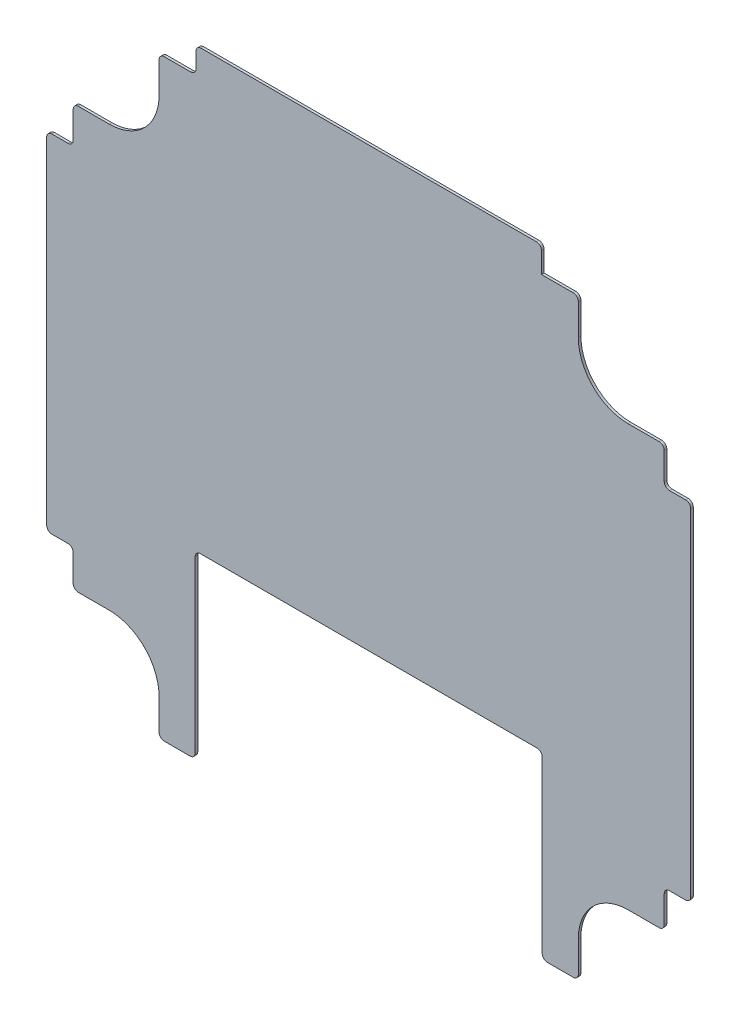
SolidWorks part; units mm, degrees
material "ABS PC"
ref_plane "Plano frontal" through (0, 0, 0) normal (0, 0, 1) x (1, 0, 0)
ref_plane "Plano superior" through (0, 0, 0) normal (0, 1, 0) x (1, 0, 0)
ref_plane "Plano direito" through (0, 0, 0) normal (1, 0, 0) x (0, 0, -1)
sketch "Esboço1" plane through (0, 0, 0) normal (0, 0, 1) x (1, 0, 0)
  line L0 (306.3428, -674.4933) -> (275.5206, -674.4933)
  line L5 (275.5206, -674.4933) -> (275.5206, -717.7786)
  line L6 (175.5581, -775.7411) -> (175.5581, -817.7411)
  line L7 (175.5581, -817.7411) -> (133.5581, -817.7411)
  line L8 (133.5581, -817.7411) -> (133.5581, -607.7411)
  line L9 (233.5206, -717.7786) -> (275.5206, -717.7786)
  line L10 (291.5428, -270.1036) -> (291.5428, -675.5786) construction
  line L12 (291.5428, -472.8411) -> (-428.2572, -472.8411) construction
  line L14 (-428.2572, -675.5786) -> (-428.2572, -472.8411) construction
  line L16 (233.5206, -227.9036) -> (275.5206, -227.9036)
  line L18 (175.5581, -127.9411) -> (133.5581, -127.9411)
  line L19 (175.5581, -169.9411) -> (175.5581, -127.9411)
  line L20 (275.5206, -271.189) -> (275.5206, -227.9036)
  line L21 (306.3428, -271.189) -> (275.5206, -271.189)
  line L23 (132.6775, -97.9411) -> (132.6775, -127.9411)
  line L24 (132.6775, -127.9411) -> (133.5581, -127.9411)
  line L26 (-68.3572, -472.8411) -> (-68.3572, -97.9411) construction
  line L27 (-428.2572, -270.1036) -> (-428.2572, -675.5786) construction
  line L28 (-269.3919, -127.9411) -> (-270.2725, -127.9411)
  line L29 (-269.3919, -97.9411) -> (-269.3919, -127.9411)
  line L30 (-443.0572, -271.189) -> (-412.235, -271.189)
  line L31 (-412.235, -271.189) -> (-412.235, -227.9036)
  line L32 (-312.2725, -169.9411) -> (-312.2725, -127.9411)
  line L33 (-312.2725, -127.9411) -> (-270.2725, -127.9411)
  line L34 (-370.235, -227.9036) -> (-412.235, -227.9036)
  line L35 (-370.235, -717.7786) -> (-412.235, -717.7786)
  line L36 (-270.2725, -817.7411) -> (-270.2725, -607.7411)
  line L37 (-312.2725, -817.7411) -> (-270.2725, -817.7411)
  line L38 (-312.2725, -775.7411) -> (-312.2725, -817.7411)
  line L39 (-412.235, -674.4933) -> (-412.235, -717.7786)
  line L40 (-443.0572, -674.4933) -> (-412.235, -674.4933)
  line L41 (-269.3919, -97.9411) -> (132.6775, -97.9411)
  line L42 (306.3428, -271.189) -> (306.3428, -674.4933)
  line L43 (-443.0572, -271.189) -> (-443.0572, -674.4933)
  line L44 (-270.2725, -607.7411) -> (133.5581, -607.7411)
  arc A0 (233.5206, -717.7786) -> (175.5581, -775.7411) centre (233.5206, -775.7411) ccw
  arc A1 (233.5206, -227.9036) -> (175.5581, -169.9411) centre (233.5206, -169.9411) cw
  arc A2 (-370.235, -227.9036) -> (-312.2725, -169.9411) centre (-370.235, -169.9411) ccw
  arc A3 (-370.235, -717.7786) -> (-312.2725, -775.7411) centre (-370.235, -775.7411) cw
  dimension "D1" = 42
  dimension "D2" = 210
  dimension "D4" = 42
extrude "Ressalto-extrusão1" add sketch "Esboço1" along normal blind 3
fillet "Filete1" radius 6 23 edges at (-443.0572, -271.189, 1.5) (-412.235, -271.189, 1.5) (-412.235, -227.9036, 1.5) (-312.2725, -127.9411, 1.5) (-269.3919, -127.9411, 1.5) (-269.3919, -97.9411, 1.5) (132.6775, -97.9411, 1.5) (175.5581, -127.9411, 1.5) (275.5206, -227.9036, 1.5) (275.5206, -271.189, 1.5) (306.3428, -271.189, 1.5) (306.3428, -674.4933, 1.5) (275.5206, -674.4933, 1.5) (275.5206, -717.7786, 1.5) (175.5581, -817.7411, 1.5) (133.5581, -817.7411, 1.5) (133.5581, -607.7411, 1.5) (-270.2725, -607.7411, 1.5) (-270.2725, -817.7411, 1.5) (-312.2725, -817.7411, 1.5) (-412.235, -717.7786, 1.5) (-412.235, -674.4933, 1.5) (-443.0572, -674.4933, 1.5)
